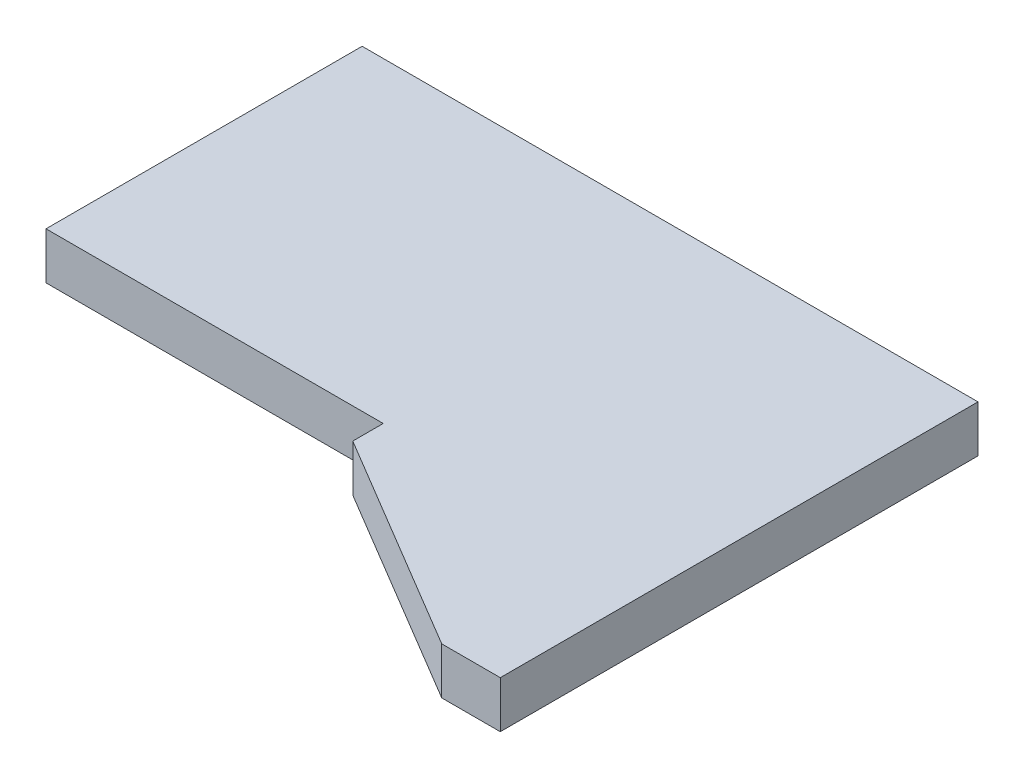
SolidWorks part; units mm, degrees
ref_plane "Front Plane" through (0, 0, 0) normal (0, 0, 1) x (1, 0, 0)
ref_plane "Top Plane" through (0, 0, 0) normal (0, 1, 0) x (1, 0, 0)
ref_plane "Right Plane" through (0, 0, 0) normal (1, 0, 0) x (0, 0, -1)
sketch "PCB" plane through (0, 0, 0) normal (0, 1, 0) x (1, 0, 0)
  line L0 (0, 0) -> (131.5, 0)
  line L1 (131.5, 0) -> (131.5, -102)
  line L2 (131.5, -102) -> (119, -102)
  line L3 (0, 0) -> (0, -67.5)
  line L4 (0, -67.5) -> (72, -67.5)
  line L5 (72, -67.5) -> (72, -74)
  line L6 (72, -74) -> (119, -102)
  point P3 (0, 0)
  dimension "D1" = 131.5
  dimension "D2" = 102
  dimension "D3" = 12.5
  dimension "D4" = 67.5
  dimension "D5" = 72
  dimension "D6" = 6.5
extrude "Boss-Extrude1" add sketch "PCB" along normal blind 10
